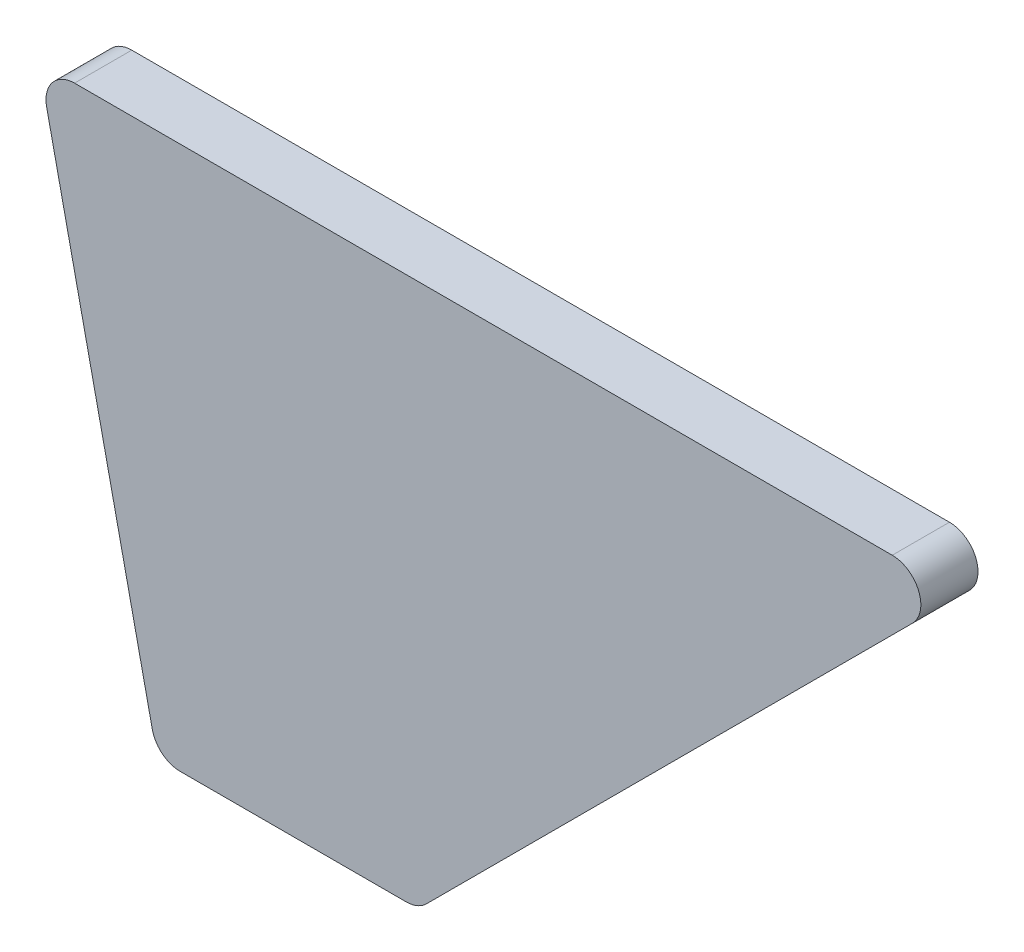
SolidWorks part; units mm, degrees
ref_plane "Ebene vorne" through (0, 0, 0) normal (0, 0, 1) x (1, 0, 0)
ref_plane "Ebene oben" through (0, 0, 0) normal (0, 1, 0) x (1, 0, 0)
ref_plane "Ebene rechts" through (0, 0, 0) normal (1, 0, 0) x (0, 0, -1)
sketch "Sketch1" plane through (0, 0, 0) normal (0, 0, 1) x (1, 0, 0)
  line L0 (-12.6729, -60.239) -> (148.5896, -60.239)
  line L1 (148.5896, -60.239) -> (53.5896, -155.239)
  line L2 (53.5896, -155.239) -> (7.9792, -155.239)
  line L3 (7.9792, -155.239) -> (-12.6729, -60.239)
  line L4 (12.0091, -155.239) -> (51.5185, -155.239) construction
  line L5 (-11.3551, -66.3012) -> (7.1232, -151.3012) construction
  line L6 (55.0541, -153.7746) -> (140.0541, -68.7746) construction
  line L7 (136.5185, -60.239) -> (-6.4692, -60.239) construction
extrude "Boss-Extrude1" add sketch "Sketch1" along normal mid plane 10
fillet "Fillet1" radius 5 4 edges at (-12.6729, -60.239, 0) (148.5896, -60.239, 0) (53.5896, -155.239, 0) (7.9792, -155.239, 0)
